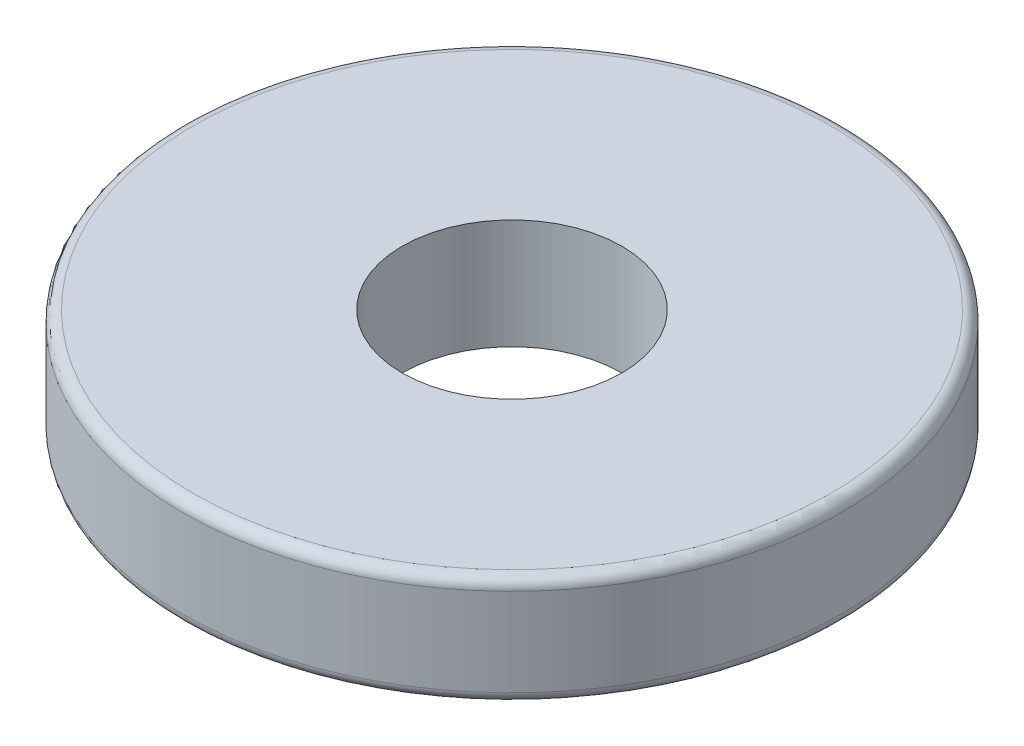
SolidWorks part; units mm, degrees
ref_plane "Ebene vorne" through (0, 0, 0) normal (0, 0, 1) x (1, 0, 0)
ref_plane "Ebene oben" through (0, 0, 0) normal (0, 1, 0) x (1, 0, 0)
ref_plane "Ebene rechts" through (0, 0, 0) normal (1, 0, 0) x (0, 0, -1)
ref_plane "Ebene1" through (0, 0, 10) normal (0, 0, 1) x (1, 0, 0)
ref_plane "Ebene2" through (0, 10, 0) normal (0, 1, 0) x (1, 0, 0)
ref_plane "Ebene3" through (10, 0, 0) normal (1, 0, 0) x (0, 0, -1)
sketch "Skizze1" plane through (0, 10, 0) normal (0, 1, 0) x (1, 0, 0)
  line L0 (-55, -10) -> (55, -10) construction
  line L1 (10, -55) -> (10, 55) construction
  circle A0 centre (10, -10) radius 30
  circle A1 centre (10, -10) radius 10
extrude "Aufsatz-Linear austragen1" add sketch "Skizze1" along normal blind 10
fillet "Verrundung1" radius 1 2 edges at (10, 10, 40) (10, 20, 40)
